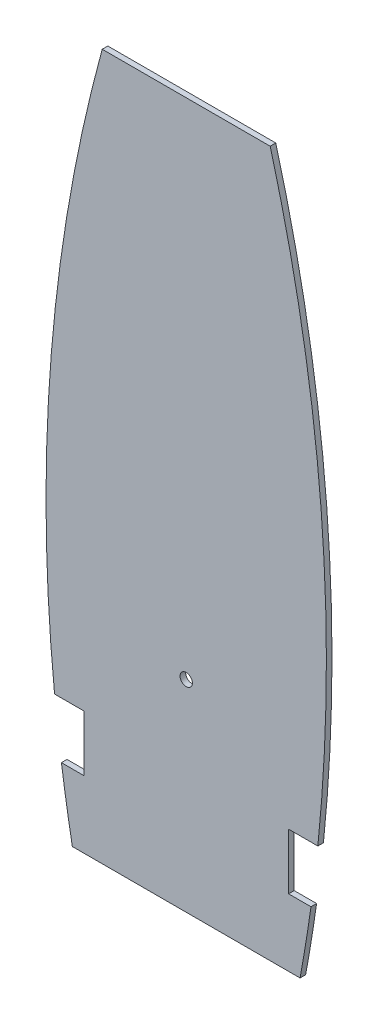
SolidWorks part; units mm, degrees
material "A-Glass Fiber"
ref_plane "Plan de face" through (0, 0, 0) normal (0, 0, 1) x (1, 0, 0)
ref_plane "Plan de dessus" through (0, 0, 0) normal (0, 1, 0) x (1, 0, 0)
ref_plane "Plan de droite" through (0, 0, 0) normal (1, 0, 0) x (0, 0, -1)
sketch "Sketch2" plane through (0, 0, 0) normal (0, 0, 1) x (1, 0, 0)
  line L0 (0, 0) -> (0, -350) construction
  line L1 (-75, 0) -> (75, 0)
  line L2 (125, -350) -> (-125, -350) construction
  line L3 (72.4663, -755.6809) -> (4.8134, -996.3531)
  line L5 (-72.4663, -755.6809) -> (-4.8134, -996.3531)
  arc A0 (75, 0) -> (72.4663, -755.6809) centre (-1287.9254, -373.2751) cw
  arc A1 (4.8134, -996.3531) -> (0, -1000) centre (0, -995) cw
  arc A2 (-75, 0) -> (-72.4663, -755.6809) centre (1287.9254, -373.2751) ccw
  arc A3 (0, -1000) -> (-4.8134, -996.3531) centre (0, -995) cw
  point P8 (0, -350)
  dimension "D3" = 5
  dimension "D1" = 350
  dimension "D2" = 250
  dimension "D4" = 250
extrude "Boss-Extrude1" add sketch "Sketch2" along normal blind 5
sketch "Sketch3" plane through (0, 0, 0) normal (0, 0, -1) x (-1, 0, 0)
  circle A0 centre (0, -450) radius 5.5
  dimension "D2" = 11
  dimension "D1" = 450
extrude "Cut-Extrude1" cut sketch "Sketch3" against normal through all
sketch "Sketch4" plane through (0, 0, 0) normal (0, 0, -1) x (-1, 0, 0)
  line L0 (-117.5538, -520) -> (-91.4313, -520)
  line L1 (-91.4313, -520) -> (-91.4313, -570)
  line L2 (-91.4313, -570) -> (-111.4313, -570)
  line L3 (-75, 0) -> (75, 0) construction
  line L4 (0, 2.75) -> (0, -2.75) construction
  line L5 (117.5538, -520) -> (91.4313, -520)
  line L6 (91.4313, -520) -> (91.4313, -570)
  line L7 (91.4313, -570) -> (111.4313, -570)
  line L8 (101.6761, -630) -> (-101.6761, -630)
  line L9 (-101.6761, -630) -> (-101.6761, -1039.9584)
  line L10 (-101.6761, -1039.9584) -> (101.6761, -1039.9584)
  line L11 (101.6761, -1039.9584) -> (101.6761, -630)
  arc A0 (-75, 0) -> (-72.4663, -755.6809) centre (1287.9254, -373.2751) ccw construction
  arc A1 (-117.5538, -520) -> (-111.4313, -570) centre (-91.4313, -542.1762) ccw
  arc A2 (117.5538, -520) -> (111.4313, -570) centre (91.4313, -542.1762) cw
  arc A3 (72.4663, -755.6809) -> (75, 0) centre (-1287.9254, -373.2751) ccw construction
  dimension "D1" = 520
  dimension "D2" = 50
  dimension "D3" = 20
  dimension "D4" = 630
extrude "Cut-Extrude2" cut sketch "Sketch4" against normal through all
sketch "Sketch6" plane through (0, 0, 0) normal (0, 0, -1) x (-1, 0, 0)
  line L5 (-55.7616, -25) -> (55.7616, -25)
  line L6 (0, 0) -> (0, -25) construction
  line L14 (-120.4836, -258.0191) -> (-95.5669, -260.0581) construction
  line L15 (-120.4836, -258.0191) -> (-108.9252, -116.7772) construction
  line L16 (-120.4836, -258.0191) -> (-95.5669, -260.0581) construction
  line L17 (-120.4836, -258.0191) -> (-135.996, -447.5778) construction
  line L21 (-98.6894, -437.5) -> (98.6894, -437.5)
  line L22 (0, 2.75) -> (0, -2.75) construction
  arc A1 (-75, 0) -> (-117.5538, -520) centre (1287.9254, -373.2751) ccw construction
  arc A5 (98.6894, -437.5) -> (55.7616, -25) centre (-1286.0087, -373.1182) ccw
  arc A6 (-98.6894, -437.5) -> (-55.7616, -25) centre (1286.0087, -373.1182) cw
  point P56 (97.3006, -462.5)
  point P57 (0, 0)
  point P58 (0, 0)
sketch "Sketch7" plane through (0, 0, 0) normal (0, 0, 1) x (1, 0, 0)
  line L0 (80.695, -605) -> (12.5, -605)
  line L1 (-80.695, -605) -> (-82.3804, -595)
  line L2 (-82.3804, -595) -> (-66.4313, -595)
  line L3 (-66.4313, -595) -> (-66.4313, -495)
  line L4 (-66.4313, -495) -> (-94.8166, -495)
  line L5 (-55.7616, -25) -> (55.7616, -25)
  line L6 (0, 0) -> (0, -25) construction
  line L7 (-92.1167, -495) -> (-92.1167, -520) construction
  line L9 (-66.4313, -545) -> (-91.4313, -545) construction
  line L11 (-82.0756, -596.8084) -> (-106.728, -600.9633) construction
  line L12 (0, -605) -> (0, -630) construction
  line L14 (-120.4836, -258.0191) -> (-95.5669, -260.0581) construction
  line L15 (-120.4836, -258.0191) -> (-108.9252, -116.7772) construction
  line L16 (-120.4836, -258.0191) -> (-95.5669, -260.0581) construction
  line L17 (-120.4836, -258.0191) -> (-135.996, -447.5778) construction
  line L18 (-97.3006, -462.5) -> (-12.5, -462.5)
  line L19 (-12.5, -462.5) -> (-12.5, -605)
  line L20 (0, -450) -> (-12.5, -462.5)
  line L21 (-98.6894, -437.5) -> (98.6894, -437.5)
  line L23 (66.4313, -495) -> (94.8166, -495)
  line L24 (97.3006, -462.5) -> (12.5, -462.5)
  line L25 (12.5, -462.5) -> (12.5, -605)
  line L26 (82.3804, -595) -> (66.4313, -595)
  line L27 (66.4313, -595) -> (66.4313, -495)
  line L28 (80.695, -605) -> (82.3804, -595)
  line L29 (-12.5, -605) -> (-80.695, -605)
  arc A2 (-94.8166, -495) -> (-97.3006, -462.5) centre (1286.0087, -373.1182) cw
  arc A4 (94.8166, -495) -> (97.3006, -462.5) centre (-1286.0087, -373.1182) ccw
  arc A5 (98.6894, -437.5) -> (55.7616, -25) centre (-1286.0087, -373.1182) ccw
  arc A6 (-98.6894, -437.5) -> (-55.7616, -25) centre (1286.0087, -373.1182) cw
  point P56 (97.3006, -462.5)
  point P57 (0, 0)
  point P58 (0, 0)
  dimension "D1" = 25
  dimension "D2" = 45
  dimension "D3" = 12.5
  dimension "D4" = 25
